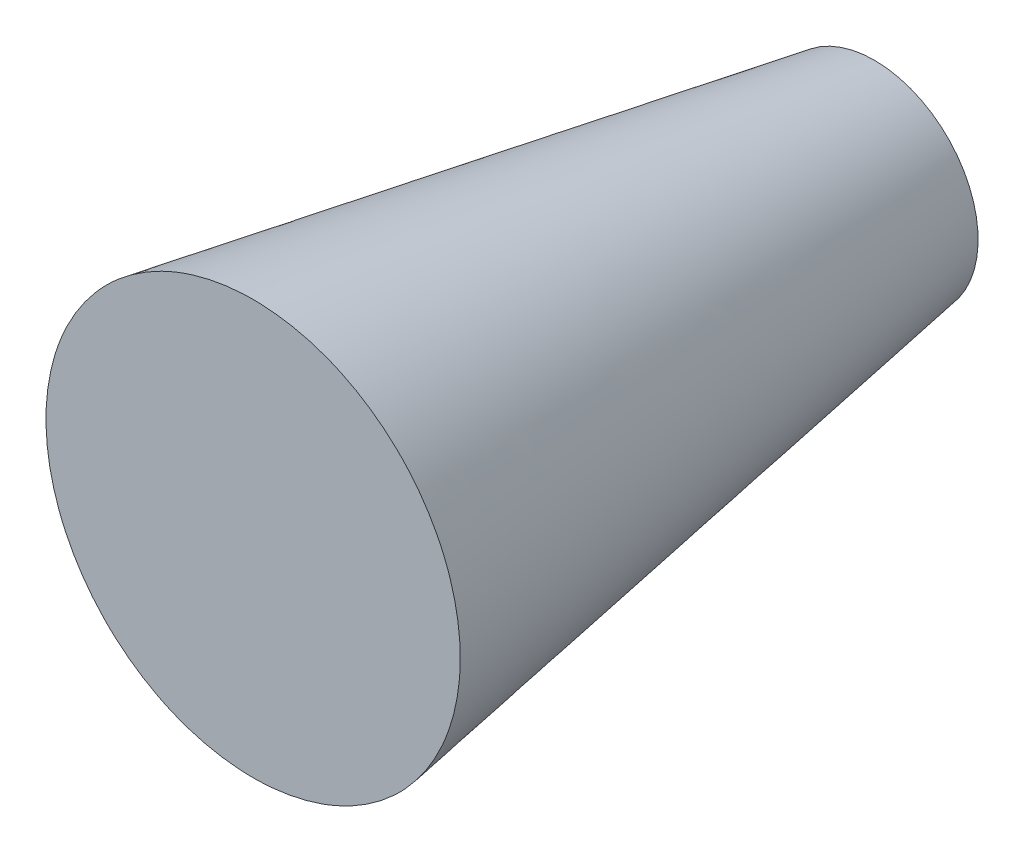
SolidWorks part; units mm, degrees
ref_plane "前视基准面" through (0, 0, 0) normal (0, 0, 1) x (1, 0, 0)
ref_plane "上视基准面" through (0, 0, 0) normal (0, 1, 0) x (1, 0, 0)
ref_plane "右视基准面" through (0, 0, 0) normal (1, 0, 0) x (0, 0, -1)
other "Configuration Table"
sketch "Profile1" plane through (0, 0, 0) normal (0, 0, 1) x (1, 0, 0)
  circle A0 centre (0, 0) radius 5
ref_plane "Plane1" through (0, 0, 15) normal (0, 0, 1) x (1, 0, 0)
sketch "Profile2" plane through (0, 0, 15) normal (0, 0, 1) x (1, 0, 0)
  circle A0 centre (0, 0) radius 7.5
ref_plane "Plane2" through (0, 0, 30) normal (0, 0, 1) x (1, 0, 0)
sketch "Profile3" plane through (0, 0, 30) normal (0, 0, 1) x (1, 0, 0)
  circle A0 centre (0, 0) radius 10
loft "modern_loft_3sections_baseline" add profiles "Profile1", "Profile2", "Profile3"
